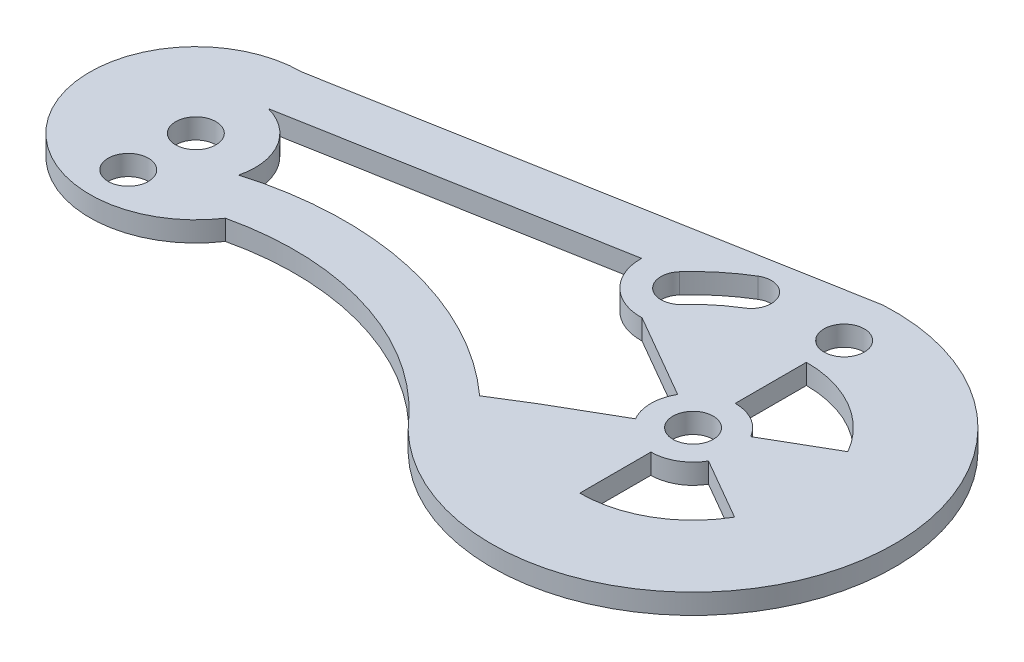
SolidWorks part; units mm, degrees
ref_plane "Front Plane" through (0, 0, 0) normal (0, 0, 1) x (1, 0, 0)
ref_plane "Top Plane" through (0, 0, 0) normal (0, 1, 0) x (1, 0, 0)
ref_plane "Right Plane" through (0, 0, 0) normal (1, 0, 0) x (0, 0, -1)
sketch "Sketch1" plane through (0, 0, 0) normal (0, 1, 0) x (1, 0, 0)
  line L0 (-33.676, 11.1806) -> (15.2114, 19.9842)
  line L1 (4.3444, 6.929) -> (16.3199, 0.0149) construction
  line L2 (16.3199, 0.0149) -> (-18.5385, 0.0149) construction
  line L3 (-32.206, 6.3649) -> (-0.7967, 12.021)
  line L4 (12.6943, 2.1082) -> (4.3444, 6.929)
  line L5 (6.5756, -5.611) -> (2.9863, -7.835)
  line L6 (16.3199, 4.2015) -> (16.3199, 11.2668)
  line L8 (19.9456, 2.1082) -> (26.0643, 5.6409)
  line L10 (19.9456, -2.0783) -> (26.0643, -5.611)
  line L12 (16.3199, -4.1716) -> (16.3199, -11.2369)
  line L14 (12.6943, -2.0783) -> (6.5756, -5.611)
  line L15 (-33.3004, 6.1678) -> (15.7734, 15.005) construction
  circle A0 centre (-33.676, 0.6496) radius 2
  arc A1 (1.2118, -13.0902) -> (15.2114, 19.9842) centre (16.3199, 0.0149) ccw
  arc A2 (12.6943, 2.1082) -> (12.6943, -2.0783) centre (16.3199, 0.0149) ccw
  arc A4 (-24.9124, -5.1898) -> (1.2118, -13.0902) centre (-18.722, -31.8627) cw
  arc A5 (-0.7967, 12.021) -> (4.3444, 6.929) centre (4.2, 11.9246) ccw
  arc A6 (-33.676, 11.1806) -> (-24.9124, -5.1898) centre (-33.676, 0.6496) ccw
  circle A7 centre (-33.8862, -5.847) radius 2
  circle A8 centre (16.3199, 0.0149) radius 2
  circle A9 centre (16.3199, 15.0149) radius 2
  arc A10 (2.2447, 12.7625) -> (5.206, 10.0805) centre (3.7254, 11.4215) ccw
  arc A11 (8.4703, 12.7906) -> (5.6248, 10.5244) centre (16.3199, 0.0149) ccw
  arc A12 (6.3788, 16.1947) -> (2.7751, 13.3247) centre (16.3199, 0.0149) ccw
  arc A13 (26.0643, 5.6409) -> (16.3199, 11.2668) centre (16.3199, 0.0149) ccw
  arc A14 (19.9456, 2.1082) -> (16.3199, 4.2015) centre (16.3199, 0.0149) ccw
  arc A15 (16.3199, -4.1716) -> (19.9456, -2.0783) centre (16.3199, 0.0149) ccw
  arc A16 (16.3199, -11.2369) -> (26.0643, -5.611) centre (16.3199, 0.0149) ccw
  arc A17 (-27.9626, -0.8274) -> (-32.206, 6.3649) centre (-33.676, 0.6496) ccw
  arc A18 (5.6248, 10.5244) -> (5.206, 10.0805) centre (16.3199, 0.0149) ccw
  arc A19 (0.6353, 15.4274) -> (7.7646, 8.4218) centre (4.2, 11.9246) ccw construction
  arc A20 (-28.3832, -0.9557) -> (4.9296, -9.7452) centre (-18.722, -31.8627) cw construction
  arc A21 (-33.3004, 6.1678) -> (-28.3832, -0.9557) centre (-33.676, 0.6496) ccw construction
  arc A22 (-27.9626, -0.8274) -> (2.9863, -7.835) centre (-18.722, -31.8627) cw
  arc A23 (2.7751, 13.3247) -> (2.2447, 12.7625) centre (16.3199, 0.0149) ccw
  arc A24 (4.8083, 18.7508) -> (0.6353, 15.4274) centre (16.3199, 0.0149) ccw construction
  arc A25 (10.0408, 10.2346) -> (4.8083, 18.7508) centre (7.4245, 14.4927) ccw construction
  arc A26 (10.0408, 10.2346) -> (7.7646, 8.4218) centre (16.3199, 0.0149) ccw construction
  arc A27 (6.3788, 16.1947) -> (6.5042, 16.2711) centre (16.3199, 0.0149) cw
  arc A28 (8.4703, 12.7906) -> (8.5694, 12.851) centre (16.3199, 0.0149) cw
  arc A29 (4.9296, -9.7452) -> (15.7734, 15.005) centre (16.3199, 0.0149) ccw construction
  arc A30 (8.5694, 12.851) -> (6.5042, 16.2711) centre (7.5368, 14.561) ccw
  arc A32 (2.7751, 13.3247) -> (5.6248, 10.5244) centre (4.2, 11.9246) ccw construction
  arc A34 (8.4703, 12.7906) -> (6.3788, 16.1947) centre (7.4245, 14.4927) ccw construction
  point P11 (-24.9124, -5.1898)
  point P12 (-33.361, 7.173)
  point P26 (16.3266, 0.0086)
  point P30 (15.6649, 16.0015)
  point P40 (-18.722, -31.8627)
  point P43 (-26.8808, -2.5969)
  point P44 (3.4406, -11.0811)
  point P47 (16.3199, 0.0149)
  point P48 (15.5543, 16.9977)
  point P51 (16.3199, 0.0149)
  point P52 (-33.4303, 8.1766)
  point P53 (-33.676, 0.6496)
  point P54 (16.3199, 0.0149)
  point P55 (4.1848, -10.4128)
  point P56 (-18.722, -31.8627)
  point P57 (-27.6079, -1.7652)
  point P58 (-33.676, 0.6496)
  dimension "D1" = 4
  dimension "D2" = 40
  dimension "D3" = 30
  dimension "D4" = 3
  dimension "D6" = 4
  dimension "D7" = 4
  dimension "D8" = 4
  dimension "D9" = 5
  dimension "D5" = 50
  dimension "D10" = 15
  dimension "D11" = 6.5
extrude "Boss-Extrude2" add sketch "Sketch1" along normal blind 2
